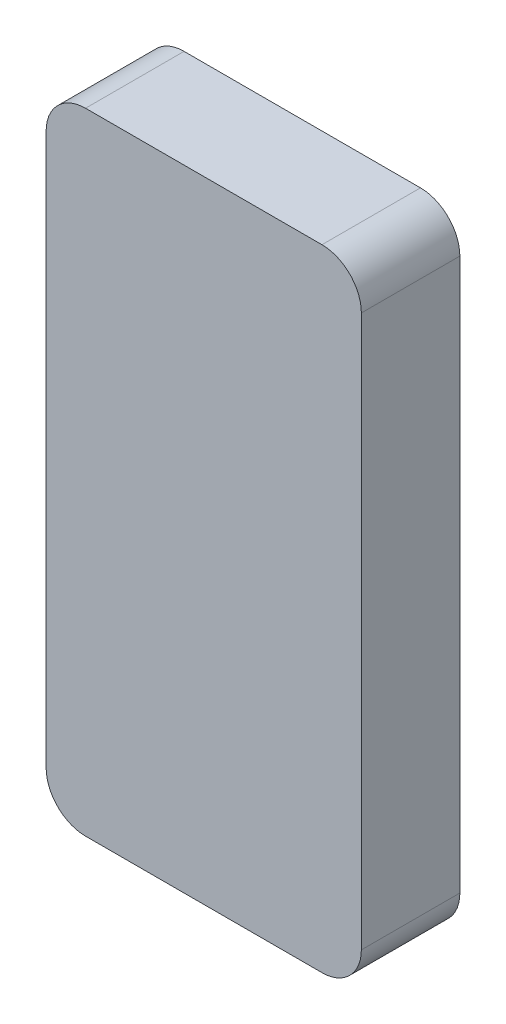
SolidWorks part; units mm, degrees
ref_plane "前视基准面" through (0, 0, 0) normal (0, 0, 1) x (1, 0, 0)
ref_plane "上视基准面" through (0, 0, 0) normal (0, 1, 0) x (1, 0, 0)
ref_plane "右视基准面" through (0, 0, 0) normal (1, 0, 0) x (0, 0, -1)
sketch "草图1" plane through (0, 0, 0) normal (0, 0, 1) x (1, 0, 0)
  line L1 (-30, -80) -> (30, -80)
  line L2 (-40, -70) -> (-40, 70)
  line L3 (-30, 80) -> (30, 80)
  line L4 (40, -70) -> (40, 70)
  line L5 (-40, -80) -> (40, 80) construction
  line L6 (-40, 80) -> (40, -80) construction
  arc A0 (30, -80) -> (40, -70) centre (30, -70) ccw
  arc A1 (-40, 70) -> (-30, 80) centre (-30, 70) cw
  arc A2 (-30, -80) -> (-40, -70) centre (-30, -70) cw
  arc A3 (30, 80) -> (40, 70) centre (30, 70) cw
  point P0 (0, 0)
  dimension "D3" = 10
  dimension "D1" = 160
  dimension "D2" = 80
extrude "凸台-拉伸1" add sketch "草图1" along normal blind 25
